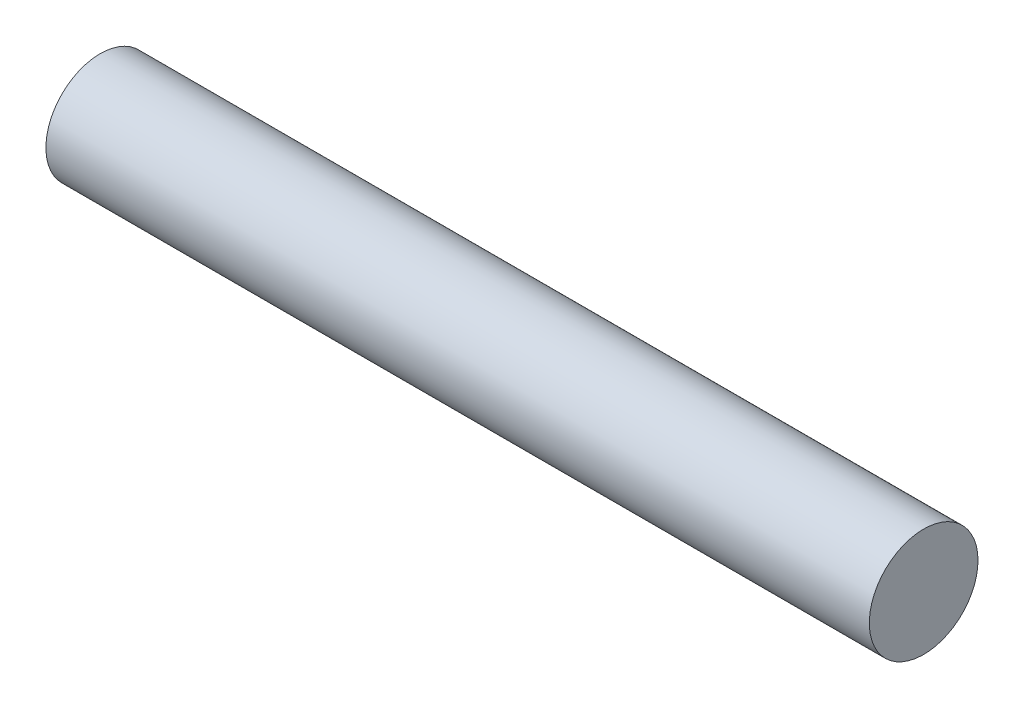
SolidWorks part; units mm, degrees
ref_plane "Alzado" through (0, 0, 0) normal (1, 0, 0) x (0, 1, 0)
ref_plane "Planta" through (0, 0, 0) normal (0, 0, 1) x (0, 1, 0)
ref_plane "Vista lateral" through (0, 0, 0) normal (0, 1, 0) x (-1, 0, 0)
sketch "Croquis2" plane through (0, 0, 0) normal (1, 0, 0) x (0, 1, 0)
  circle A0 centre (0, 0) radius 25.146
extrude "Saliente-Extruir1" add sketch "Croquis2" along normal blind 381
